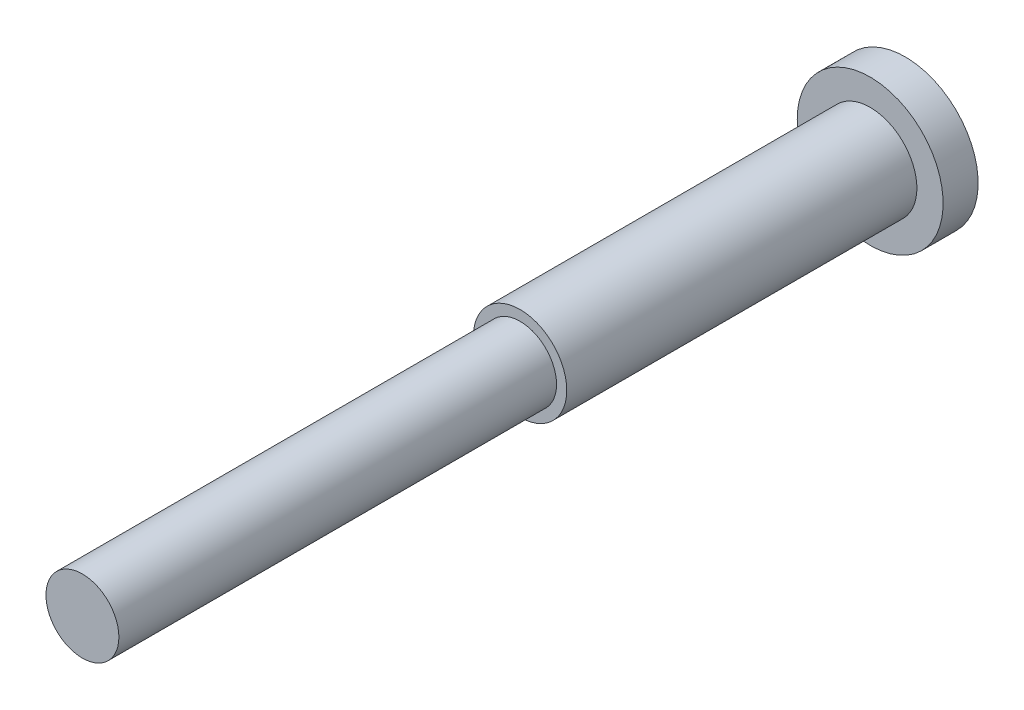
SolidWorks part; units mm, degrees
material "PW20:29:Sc:0:"
ref_plane "Front" through (0, 0, 0) normal (0, 0, 1) x (1, 0, 0)
ref_plane "Top" through (0, 0, 0) normal (0, 1, 0) x (1, 0, 0)
ref_plane "Right" through (0, 0, 0) normal (1, 0, 0) x (0, 0, -1)
sketch "Sketch1" plane through (0, 0, 0) normal (0, 0, 1) x (1, 0, 0)
  circle A0 centre (0, 0) radius 8
  dimension "D1" = 16
extrude "Base-Extrude" add sketch "Sketch1" along normal blind 60
sketch "Sketch2" plane through (0, 0, 60) normal (0, 0, 1) x (1, 0, 0)
  circle A0 centre (0, 0) radius 6.25
  dimension "D1" = 12.5
extrude "Boss-Extrude1" add sketch "Sketch2" along normal blind 75
sketch "Sketch3" plane through (0, 0, 0) normal (0, 0, -1) x (-1, 0, 0)
  circle A0 centre (0, 0) radius 12.5
  dimension "D1" = 25
extrude "Boss-Extrude2" add sketch "Sketch3" along normal blind 6
ref_plane "Place" through (0, 0, 55) normal (0, 0, 1) x (1, 0, 0)
